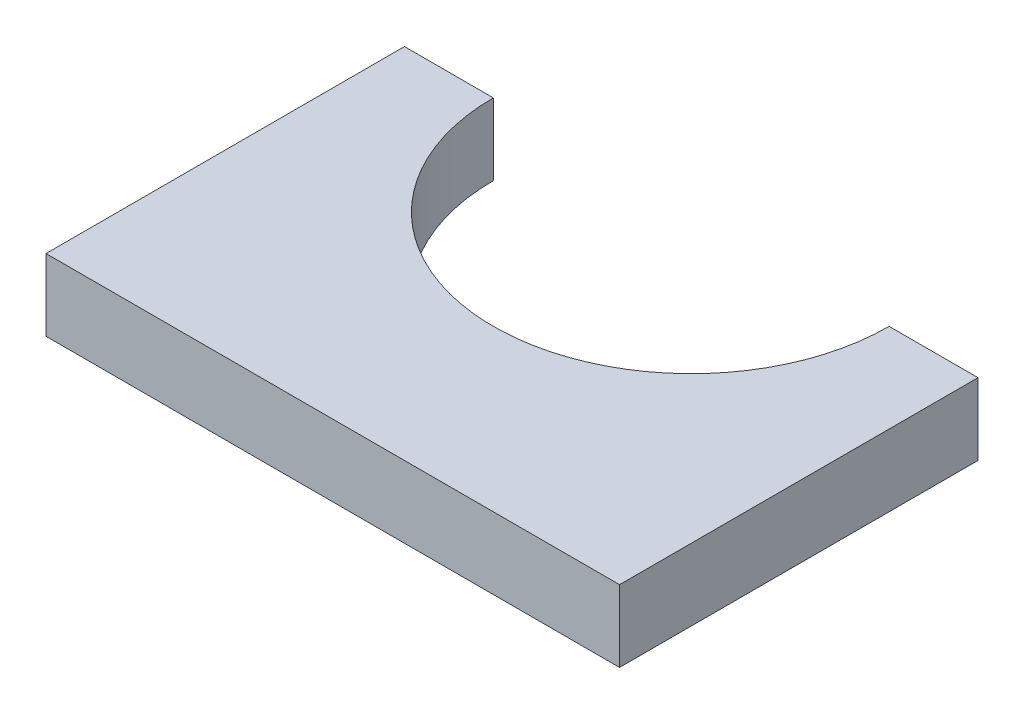
SolidWorks part; units mm, degrees
material "ABS PC"
ref_plane "Front Plane" through (0, 0, 0) normal (0, 0, 1) x (1, 0, 0)
ref_plane "Top Plane" through (0, 0, 0) normal (0, 1, 0) x (1, 0, 0)
ref_plane "Right Plane" through (0, 0, 0) normal (1, 0, 0) x (0, 0, -1)
sketch "Sketch1" plane through (0, 0, 0) normal (0, 1, 0) x (1, 0, 0)
  line L1 (-25.4, -15.875) -> (25.4, -15.875)
  line L2 (-25.4, -15.875) -> (-25.4, 15.875)
  line L3 (-25.4, 15.875) -> (25.4, 15.875)
  line L4 (25.4, -15.875) -> (25.4, 15.875)
  line L5 (-25.4, -15.875) -> (25.4, 15.875) construction
  line L6 (-25.4, 15.875) -> (25.4, -15.875) construction
  point P0 (0, 0)
  dimension "D1" = 50.8
  dimension "D2" = 31.75
extrude "Boss-Extrude1" add sketch "Sketch1" along normal blind 6.35
sketch "Sketch2" plane through (0, 6.35, 0) normal (0, 1, 0) x (1, 0, 0)
  line L0 (25.4, 15.875) -> (-25.4, 15.875) construction
  line L1 (-17.526, 15.875) -> (17.526, 15.875)
  arc A0 (17.526, 15.875) -> (-17.526, 15.875) centre (0, 15.875) cw
  dimension "D1" = 17.526
extrude "Cut-Extrude1" cut sketch "Sketch2" against normal blind 6.35
